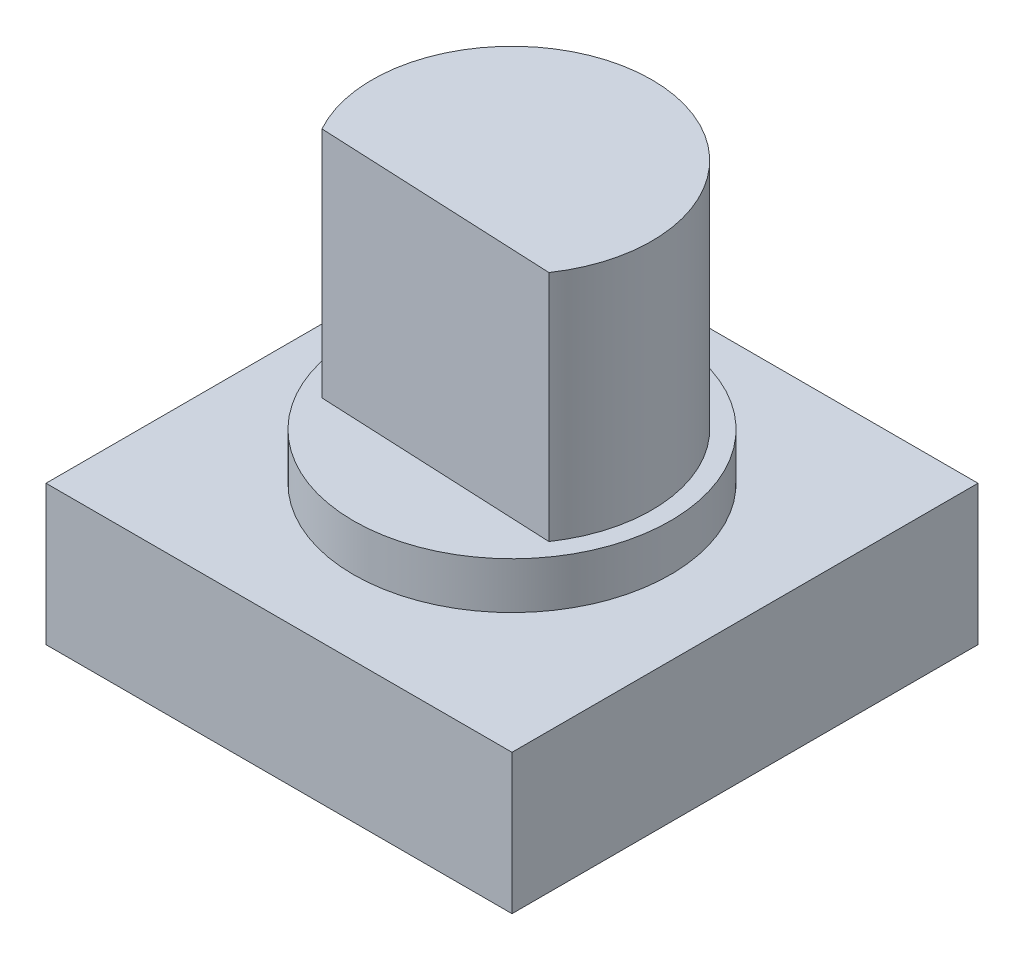
SolidWorks part; units mm, degrees
ref_plane "前视基准面" through (0, 0, 0) normal (0, 0, 1) x (1, 0, 0)
ref_plane "上视基准面" through (0, 0, 0) normal (0, 1, 0) x (1, 0, 0)
ref_plane "右视基准面" through (0, 0, 0) normal (1, 0, 0) x (0, 0, -1)
sketch "草图1" plane through (0, 0, 0) normal (0, 1, 0) x (1, 0, 0)
  line L1 (-5.3731, 2.6493) -> (4.6269, 2.6493)
  line L2 (-5.3731, 2.6493) -> (-5.3731, -7.3507)
  line L3 (-5.3731, -7.3507) -> (4.6269, -7.3507)
  line L4 (4.6269, 2.6493) -> (4.6269, -7.3507)
  line L5 (-5.3731, 2.6493) -> (4.6269, -7.3507) construction
  line L6 (-5.3731, -7.3507) -> (4.6269, 2.6493) construction
  point P4 (-0.3731, -2.3507)
  dimension "D1" = 10
  dimension "D2" = 10
extrude "凸台-拉伸1" add sketch "草图1" along normal blind 3
sketch "草图2" plane through (0, 3, 0) normal (0, 1, 0) x (1, 0, 0)
  line L0 (-5.3731, -2.3507) -> (4.6269, -2.3507) construction
  line L1 (-5.3731, 2.6493) -> (-5.3731, -7.3507) construction
  line L2 (4.6269, -7.3507) -> (4.6269, 2.6493) construction
  line L3 (-0.3731, 2.6493) -> (-0.3731, -7.3507) construction
  line L4 (4.6269, 2.6493) -> (-5.3731, 2.6493) construction
  line L5 (-5.3731, -7.3507) -> (4.6269, -7.3507) construction
  circle A0 centre (-0.3731, -2.3507) radius 3.4
  dimension "D1" = 6.8
extrude "凸台-拉伸2" add sketch "草图2" along normal blind 1
sketch "草图3" plane through (0, 4, 0) normal (0, 1, 0) x (1, 0, 0)
  line L0 (-2.9974, -3.8044) -> (2.1069, -4.0388)
  arc A0 (2.1069, -4.0388) -> (-2.9974, -3.8044) centre (-0.3731, -2.3507) ccw
  dimension "D1" = 6
extrude "凸台-拉伸3" add sketch "草图3" along normal blind 5
